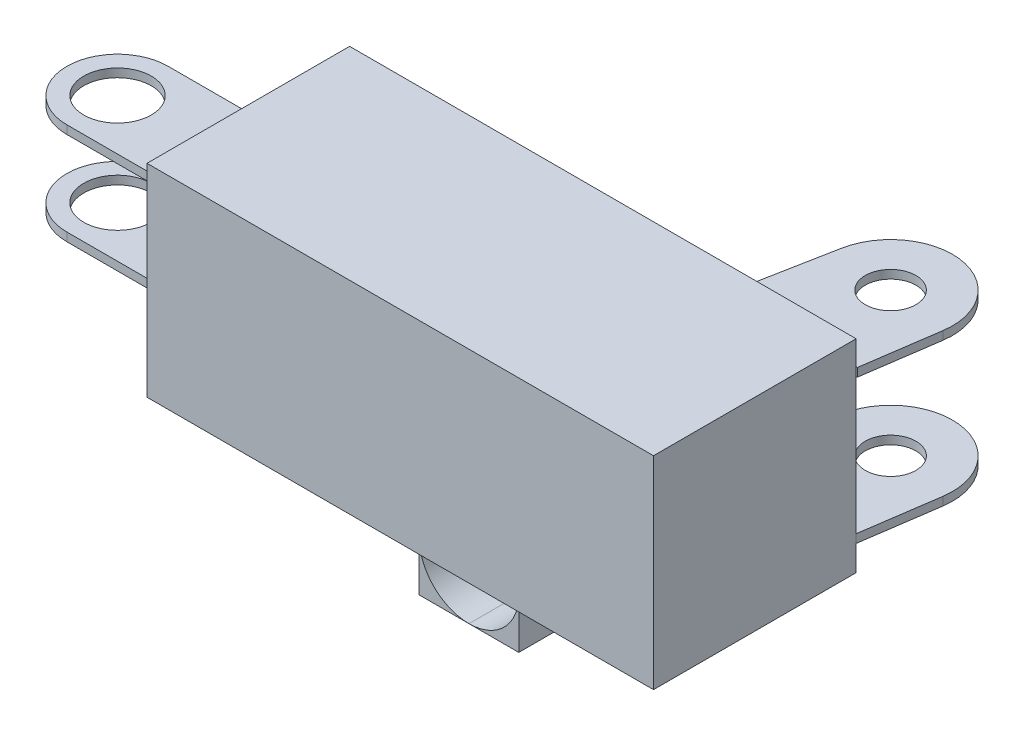
SolidWorks part; units mm, degrees
ref_plane "前视基准面" through (0, 0, 0) normal (0, 0, 1) x (1, 0, 0)
ref_plane "上视基准面" through (0, 0, 0) normal (0, 1, 0) x (1, 0, 0)
ref_plane "右视基准面" through (0, 0, 0) normal (1, 0, 0) x (0, 0, -1)
sketch "草图1" plane through (0, 0, 0) normal (0, 0, 1) x (1, 0, 0)
  line L1 (-150, -60) -> (150, -60)
  line L2 (-150, -60) -> (-150, 60)
  line L3 (-150, 60) -> (150, 60)
  line L4 (150, -60) -> (150, 60)
  line L5 (-150, -60) -> (150, 60) construction
  line L6 (-150, 60) -> (150, -60) construction
  point P0 (0, 0)
  dimension "D1" = 120
  dimension "D2" = 300
extrude "凸台-拉伸1" add sketch "草图1" along normal blind 120
sketch "草图2" plane through (0, 0, 0) normal (0, 0, -1) x (-1, 0, 0)
  line L0 (-150, 0) -> (45.6831, 0) construction
  line L1 (-150, -60) -> (-150, 60) construction
  line L2 (-145.5794, 0) -> (-145.5794, -45) construction
sketch "草图3" plane through (0, 0, 0) normal (0, 0, -1) x (-1, 0, 0)
  line L0 (-145.5794, -45) -> (-84.5609, -45)
ref_plane "基准面4" through (0, -45, 0) normal (0, -1, 0) x (-1, 0, 0)
sketch "草图4" plane through (0, -45, 0) normal (0, -1, 0) x (-1, 0, 0)
  line L0 (-156.5272, 44.911) -> (-150, 0)
  line L1 (-84.219, 57.0651) -> (-73.3189, 0)
  line L2 (-150, 0) -> (45.6831, 0) construction
  line L5 (-73.3189, 0) -> (-150, 0)
  circle A0 centre (-120.2381, 50.1851) radius 15
  arc A1 (-156.5272, 44.911) -> (-84.219, 57.0651) centre (-120.2381, 50.1851) cw
  dimension "D1" = 30
extrude "凸台-拉伸2" add sketch "草图4" against normal blind 5
sketch "草图7" plane through (0, 0, 0) normal (0, 0, -1) x (-1, 0, 0)
  line L0 (-145.5794, 0) -> (-145.5794, 45)
  line L1 (-145.5794, 45) -> (-67.705, 45)
  dimension "D1" = 45
ref_plane "基准面5" through (0, 45, 0) normal (0, 1, 0) x (1, 0, 0)
sketch "草图8" plane through (0, 45, 0) normal (0, 1, 0) x (1, 0, 0)
  line L0 (84.219, 57.0651) -> (73.3189, 0)
  line L1 (156.5272, 44.911) -> (150.1009, 0.694)
  line L2 (156.5272, 44.911) -> (150, 0) construction
  line L3 (73.3189, 0) -> (150.1009, 0.694)
  arc A0 (156.5272, 44.911) -> (84.219, 57.0651) centre (120.2381, 50.1851) ccw
  arc A1 (156.5272, 44.911) -> (84.219, 57.0651) centre (120.2381, 50.1851) ccw construction
  circle A2 centre (120.2381, 50.1851) radius 15
extrude "凸台-拉伸3" add sketch "草图8" against normal blind 5 separate body
sketch "草图9" plane through (-150, 0, 0) normal (-1, 0, 0) x (0, 0, 1)
  line L0 (0, 0) -> (127.9525, 0) construction
  line L1 (0, 60) -> (0, -60) construction
  line L2 (63.9762, 37.6256) -> (63.9762, -41.2111) construction
  line L4 (33.9762, -30) -> (93.9762, -30)
  line L5 (33.9762, -30) -> (33.9762, 30)
  line L6 (33.9762, 30) -> (93.9762, 30)
  line L7 (93.9762, -30) -> (93.9762, 30)
  line L8 (33.9762, -30) -> (93.9762, 30) construction
  line L9 (33.9762, 30) -> (93.9762, -30) construction
  point P6 (63.9762, 0)
  dimension "D1" = 60
extrude "凸台-拉伸4" add sketch "草图9" along normal blind 10
sketch "草图10" plane through (0, -30, 0) normal (0, -1, 0) x (1, 0, 0)
  line L0 (-223.4933, 93.9762) -> (-160, 93.9762)
  line L2 (-223.4933, 33.9762) -> (-160, 33.9762)
  line L3 (-160, 93.9762) -> (-160, 33.9762)
  arc A0 (-223.4933, 33.9762) -> (-223.4933, 93.9762) centre (-223.4933, 63.9762) cw
  circle A1 centre (-223.4933, 63.9762) radius 20
  line M8 (-160, 93.9762) -> (-160, 33.9762)
  dimension "D1" = 40
extrude "凸台-拉伸6" add sketch "草图10" against normal blind 5 contours A0 L2 L0 A1 M8
sketch "草图11" plane through (0, 30, 0) normal (0, 1, 0) x (1, 0, 0)
  line L0 (-223.4933, -33.9762) -> (-160, -33.9762)
  line L1 (-160, -33.9762) -> (-160, -93.9762)
  line L2 (-160, -93.9762) -> (-223.4933, -93.9762)
  arc A0 (-223.4933, -33.9762) -> (-223.4933, -93.9762) centre (-223.4933, -63.9762) ccw
  arc A1 (-223.4933, -33.9762) -> (-223.4933, -93.9762) centre (-223.4933, -63.9762) ccw construction
  circle A2 centre (-223.4933, -63.9762) radius 20
extrude "凸台-拉伸7" add sketch "草图11" against normal blind 5
sketch "草图12" plane through (0, -60, 0) normal (0, -1, 0) x (1, 0, 0)
  line L1 (-27.001, 22.7929) -> (31.999, 22.7929)
  line L2 (-27.001, 22.7929) -> (-27.001, 81.7929)
  line L3 (-27.001, 81.7929) -> (31.999, 81.7929)
  line L4 (31.999, 22.7929) -> (31.999, 81.7929)
  line L5 (-27.001, 22.7929) -> (31.999, 81.7929) construction
  line L6 (-27.001, 81.7929) -> (31.999, 22.7929) construction
  point P0 (2.499, 52.2929)
  dimension "D1" = 59
extrude "凸台-拉伸8" add sketch "草图12" along normal blind 59
sketch "草图13" plane through (0, 0, 81.7929) normal (0, 0, 1) x (1, 0, 0)
  circle A0 centre (2.499, -89.5) radius 29.5
  dimension "D1" = 59
extrude "切除-拉伸2" cut sketch "草图13" against normal blind 59 contours A0
